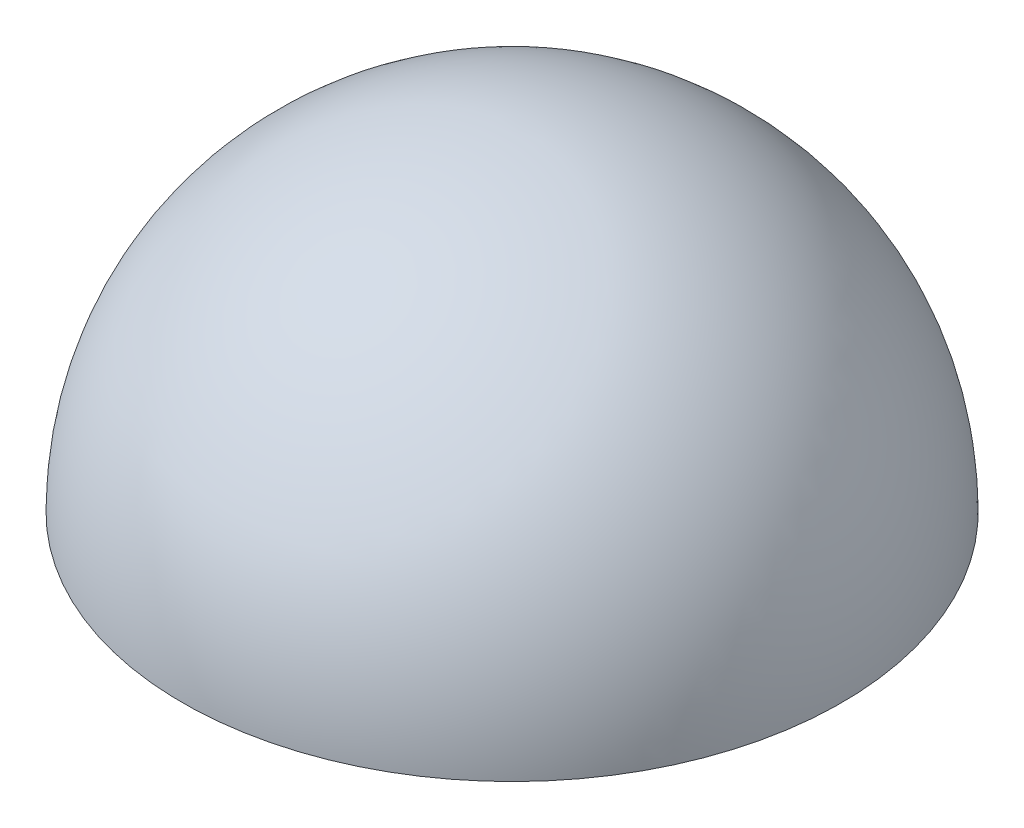
SolidWorks part; units mm, degrees
ref_plane "Front Plane" through (0, 0, 0) normal (0, 0, 1) x (1, 0, 0)
ref_plane "Top Plane" through (0, 0, 0) normal (0, 1, 0) x (1, 0, 0)
ref_plane "Right Plane" through (0, 0, 0) normal (1, 0, 0) x (0, 0, -1)
sketch "Sketch3" plane through (0, 0, 0) normal (0, 1, 0) x (1, 0, 0)
  line L0 (-40, 0) -> (40, 0)
  arc A0 (40, 0) -> (-40, 0) centre (0, 0) ccw
  dimension "D1" = 80
revolve "Revolve1" add sketch "Sketch3" angle 180 about L0
shell "Shell2" thickness 1.2
sketch "Sketch4" plane through (0, 0, 0) normal (0, -1, 0) x (1, 0, 0)
  line L0 (-39.4015, 0.6) -> (-39.4015, -0.6)
  line L1 (-39.9955, -0.6) -> (-23.0954, -0.6) construction
  line L2 (-39.9955, -0.6) -> (-39.9955, 0.6) construction
  line L3 (-39.9955, 0.6) -> (-23.0954, 0.6) construction
  line L4 (39.9955, -0.6) -> (39.9955, 0.6) construction
  line L5 (-0.6, -39.9955) -> (0.6, -39.9955) construction
  line L6 (-0.6, -39.9955) -> (-0.6, -23.0954) construction
  line L7 (-0.6, 39.9955) -> (0.6, 39.9955) construction
  line L8 (0.6, -39.9955) -> (0.6, -23.0954) construction
  line L9 (39.1, 0.6) -> (39.1, -0.6)
  line L10 (-0.6, -39.1) -> (0.6, -39.1)
  line L11 (-0.6, 39.1) -> (0.6, 39.1)
  line L12 (-39.4015, 0.6) -> (-23.0954, 0.6)
  line L13 (-0.6, 23.0954) -> (-0.6, 39.1)
  line L14 (0.6, 39.1) -> (0.6, 23.0954)
  line L15 (23.0954, 0.6) -> (39.1, 0.6)
  line L16 (39.1, -0.6) -> (23.0954, -0.6)
  line L17 (0.6, -23.0954) -> (0.6, -39.1)
  line L18 (-0.6, -39.1) -> (-0.6, -23.0954)
  line L19 (-23.0954, -0.6) -> (-39.4015, -0.6)
  line L21 (-0.6, 23.0954) -> (0.6, 23.0954)
  line L22 (-23.0954, 0.6) -> (-23.0954, -0.6)
  line L23 (-0.6, -23.0954) -> (0.6, -23.0954)
  line L24 (23.0954, 0.6) -> (23.0954, -0.6)
  line L25 (-0.6, 23.0954) -> (-0.6, 39.9955) construction
  line L26 (0.6, 23.0954) -> (0.6, 39.9955) construction
  line L27 (23.0954, 0.6) -> (39.9955, 0.6) construction
  line L28 (23.0954, -0.6) -> (39.9955, -0.6) construction
  circle A0 centre (0, 0) radius 40 construction
  circle A2 centre (0, 0) radius 38.8 construction
  point P26 (-38.7954, 0.6)
  point P28 (0.6, 38.7954)
  point P29 (-0.6, -38.7954)
  point P33 (38.7954, 0.6)
  dimension "D1" = 1.2
  dimension "D2" = 1.2
  dimension "D3" = 38.5
  dimension "D4" = 38.5
  dimension "D5" = 38.5
  dimension "D6" = 38.8015
  dimension "D7" = 15.7
  dimension "D8" = 15.7
  dimension "D9" = 15.7
  dimension "D10" = 15.7
extrude "Boss-Extrude1" add sketch "Sketch4" against normal blind 1
sketch "Sketch5" plane through (0, 0, 0) normal (0, -1, 0) x (1, 0, 0)
  line L0 (0.6, 23.0954) -> (0.6, 38.7954) construction
  line L1 (-0.6, 23.0954) -> (0.6, 23.0954)
  line L2 (-0.6, 23.0954) -> (-0.6, 24.0954)
  line L3 (-0.6, 24.0954) -> (0.6, 24.0954)
  line L4 (0.6, 23.0954) -> (0.6, 24.0954)
  line L5 (-38.7954, -0.6) -> (-23.0954, -0.6) construction
  line L6 (-23.0954, 0.6) -> (-24.0954, 0.6)
  line L7 (-23.0954, 0.6) -> (-23.0954, -0.6)
  line L8 (-23.0954, -0.6) -> (-24.0954, -0.6)
  line L9 (-24.0954, 0.6) -> (-24.0954, -0.6)
  line L16 (23.0954, -0.6) -> (38.7954, -0.6) construction
  line L17 (23.0954, 0.6) -> (24.0954, 0.6)
  line L18 (23.0954, 0.6) -> (23.0954, -0.6)
  line L19 (23.0954, -0.6) -> (24.0954, -0.6)
  line L20 (24.0954, 0.6) -> (24.0954, -0.6)
  line L21 (0.6, -38.7954) -> (0.6, -23.0954) construction
  line L22 (-0.6, -23.0954) -> (0.6, -23.0954)
  line L23 (-0.6, -23.0954) -> (-0.6, -24.0954)
  line L24 (-0.6, -24.0954) -> (0.6, -24.0954)
  line L25 (0.6, -23.0954) -> (0.6, -24.0954)
  dimension "D1" = 1
  dimension "D2" = 1
  dimension "D3" = 1
  dimension "D4" = 1
extrude "Boss-Extrude2" add sketch "Sketch5" along normal blind 5
